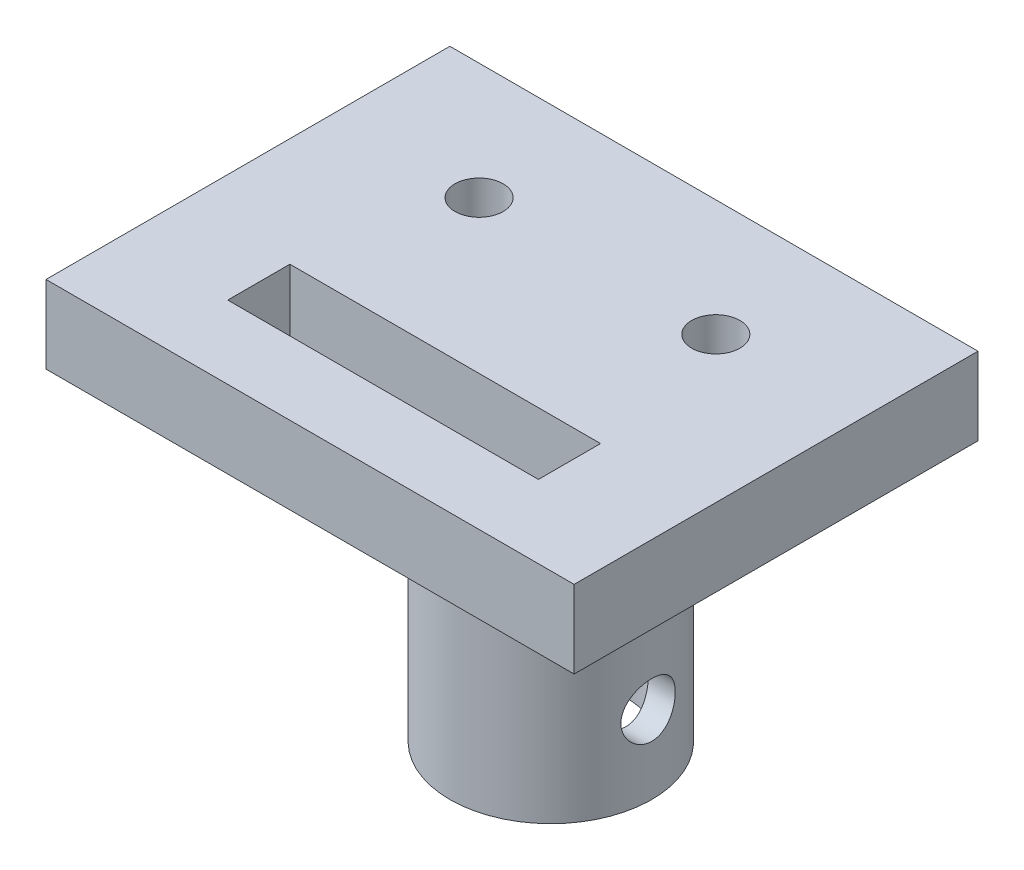
SolidWorks part; units mm, degrees
ref_plane "Front Plane" through (0, 0, 0) normal (0, 0, 1) x (1, 0, 0)
ref_plane "Top Plane" through (0, 0, 0) normal (0, 1, 0) x (1, 0, 0)
ref_plane "Right Plane" through (0, 0, 0) normal (1, 0, 0) x (0, 0, -1)
sketch "Sketch1" plane through (0, 0, 0) normal (0, 1, 0) x (1, 0, 0)
  circle A0 centre (0, 0) radius 4.85
  circle A1 centre (0, 0) radius 6.5
  dimension "D1" = 9.7
  dimension "D2" = 13
extrude "Boss-Extrude1" add sketch "Sketch1" along normal blind 25
sketch "Sketch2" plane through (0, 25, 0) normal (0, 1, 0) x (1, 0, 0)
  line L1 (-17, 10.5) -> (17, 10.5)
  line L2 (-17, 10.5) -> (-17, -15.5)
  line L3 (-17, -15.5) -> (17, -15.5)
  line L4 (17, 10.5) -> (17, -15.5)
  line L5 (-17, 10.5) -> (17, -15.5) construction
  line L6 (-17, -15.5) -> (17, 10.5) construction
  point P0 (0, -2.5)
  dimension "D1" = 26
  dimension "D2" = 34
  dimension "D3" = 2.5
extrude "Boss-Extrude2" add sketch "Sketch2" against normal blind 5
sketch "Sketch3" plane through (0, 20, 0) normal (0, -1, 0) x (-1, 0, 0)
  line L0 (-7.62, 3) -> (7.62, 3) construction
  line L1 (0, -8.8) -> (0, 3) construction
  line L2 (-10, -6.8) -> (10, -6.8)
  line L3 (-10, -6.8) -> (-10, -10.8)
  line L4 (-10, -10.8) -> (10, -10.8)
  line L5 (10, -6.8) -> (10, -10.8)
  line L6 (-10, -6.8) -> (10, -10.8) construction
  line L7 (-10, -10.8) -> (10, -6.8) construction
  circle A0 centre (-7.62, 3) radius 1.55
  circle A1 centre (7.62, 3) radius 1.55
  point P4 (0, 3)
  point P5 (0, -8.8)
  dimension "D1" = 3.1
  dimension "D2" = 15.24
  dimension "D3" = 11.8
  dimension "D4" = 4
  dimension "D5" = 20
  dimension "D6" = 3
extrude "Cut-Extrude1" cut sketch "Sketch3" along normal through all both and the other way through all
sketch "Sketch4" plane through (17, 0, 0) normal (1, 0, 0) x (0, 0, -1)
  circle A0 centre (0, 5) radius 1.75
  dimension "D1" = 5
  dimension ".3" = 3.5
extrude "Cut-Extrude2" cut sketch "Sketch4" against normal through all both and the other way through all
